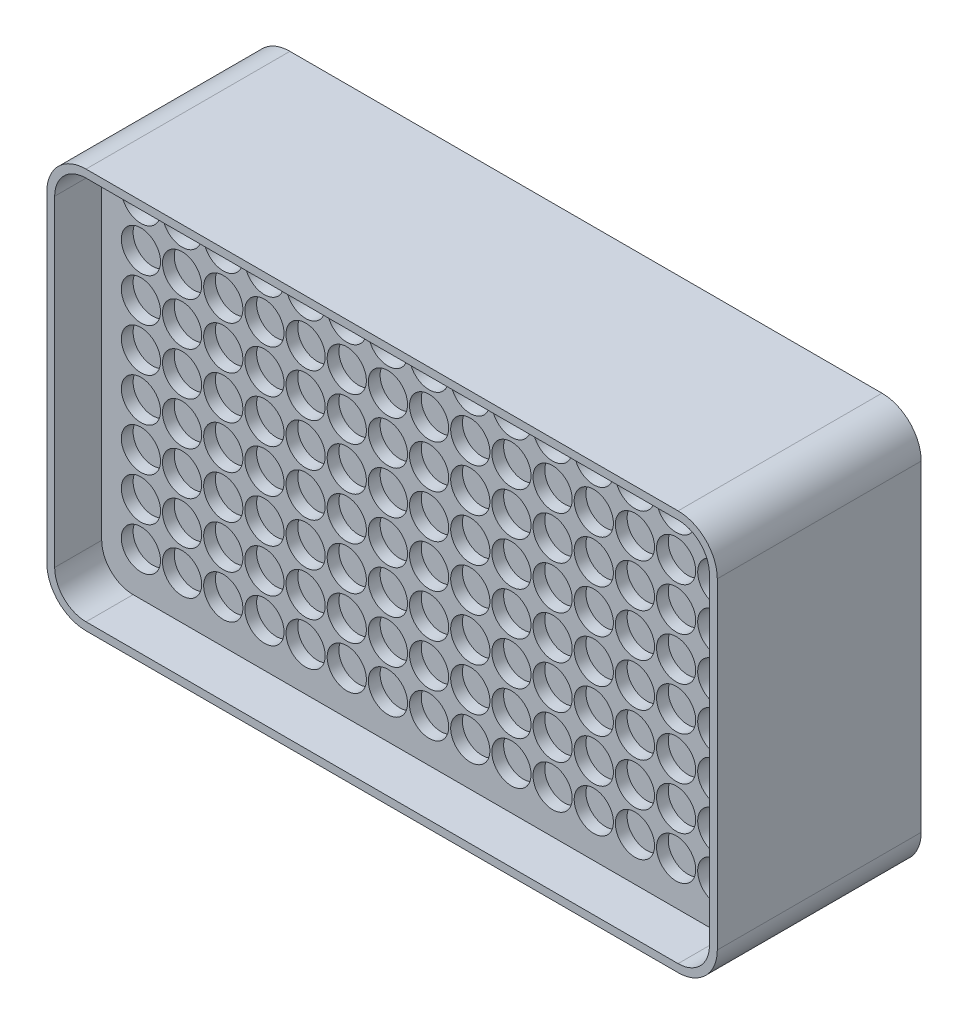
SolidWorks part; units mm, degrees
ref_plane "Front Plane" through (0, 0, 0) normal (0, 0, 1) x (1, 0, 0)
ref_plane "Top Plane" through (0, 0, 0) normal (0, 1, 0) x (1, 0, 0)
ref_plane "Right Plane" through (0, 0, 0) normal (1, 0, 0) x (0, 0, -1)
sketch "Sketch1" plane through (0, 0, 0) normal (0, 0, 1) x (1, 0, 0)
  line L1 (85.5, 51) -> (-85.5, 51)
  line L2 (85.5, 51) -> (85.5, -51)
  line L3 (85.5, -51) -> (-85.5, -51)
  line L4 (-85.5, 51) -> (-85.5, -51)
  line L5 (85.5, 51) -> (-85.5, -51) construction
  line L6 (85.5, -51) -> (-85.5, 51) construction
  point P0 (0, 0)
  dimension "D1" = 171
  dimension "D2" = 102
extrude "Boss-Extrude1" add sketch "Sketch1" along normal blind 40
fillet "Fillet1" radius 10 4 edges at (85.5, -51, 20) (85.5, 51, 20) (-85.5, -51, 20) (-85.5, 51, 20)
sketch "Sketch3" plane through (0, 0, 40) normal (0, 0, 1) x (1, 0, 0)
  line L0 (75.5, 51) -> (-75.5, 51) construction
  line L1 (-85.5, 41) -> (-85.5, -41) construction
  line L2 (-73.5, 39) -> (-63, 39) construction
  circle A0 centre (-73.5, 39) radius 5
  circle A1 centre (-63, 39) radius 5
  circle A2 centre (-52.5, 39) radius 5
  circle A3 centre (-42, 39) radius 5
  circle A4 centre (-31.5, 39) radius 5
  circle A5 centre (-21, 39) radius 5
  circle A6 centre (-10.5, 39) radius 5
  circle A7 centre (0, 39) radius 5
  circle A8 centre (10.5, 39) radius 5
  circle A9 centre (21, 39) radius 5
  circle A10 centre (31.5, 39) radius 5
  circle A11 centre (42, 39) radius 5
  circle A12 centre (52.5, 39) radius 5
  circle A13 centre (63, 39) radius 5
  circle A14 centre (73.5, 39) radius 5
  circle A15 centre (-63, 28) radius 5
  circle A16 centre (-52.5, 28) radius 5
  circle A17 centre (-42, 28) radius 5
  circle A18 centre (-31.5, 28) radius 5
  circle A19 centre (-21, 28) radius 5
  circle A20 centre (-10.5, 28) radius 5
  circle A21 centre (0, 28) radius 5
  circle A22 centre (10.5, 28) radius 5
  circle A23 centre (21, 28) radius 5
  circle A24 centre (31.5, 28) radius 5
  circle A25 centre (42, 28) radius 5
  circle A26 centre (52.5, 28) radius 5
  circle A27 centre (63, 28) radius 5
  circle A28 centre (73.5, 28) radius 5
  circle A29 centre (-63, 17) radius 5
  circle A30 centre (-52.5, 17) radius 5
  circle A31 centre (-42, 17) radius 5
  circle A32 centre (-31.5, 17) radius 5
  circle A33 centre (-21, 17) radius 5
  circle A34 centre (-10.5, 17) radius 5
  circle A35 centre (0, 17) radius 5
  circle A36 centre (10.5, 17) radius 5
  circle A37 centre (21, 17) radius 5
  circle A38 centre (31.5, 17) radius 5
  circle A39 centre (42, 17) radius 5
  circle A40 centre (52.5, 17) radius 5
  circle A41 centre (63, 17) radius 5
  circle A42 centre (73.5, 17) radius 5
  circle A43 centre (-63, 6) radius 5
  circle A44 centre (-52.5, 6) radius 5
  circle A45 centre (-42, 6) radius 5
  circle A46 centre (-31.5, 6) radius 5
  circle A47 centre (-21, 6) radius 5
  circle A48 centre (-10.5, 6) radius 5
  circle A49 centre (0, 6) radius 5
  circle A50 centre (10.5, 6) radius 5
  circle A51 centre (21, 6) radius 5
  circle A52 centre (31.5, 6) radius 5
  circle A53 centre (42, 6) radius 5
  circle A54 centre (52.5, 6) radius 5
  circle A55 centre (63, 6) radius 5
  circle A56 centre (73.5, 6) radius 5
  circle A57 centre (-63, -5) radius 5
  circle A58 centre (-52.5, -5) radius 5
  circle A59 centre (-42, -5) radius 5
  circle A60 centre (-31.5, -5) radius 5
  circle A61 centre (-21, -5) radius 5
  circle A62 centre (-10.5, -5) radius 5
  circle A63 centre (0, -5) radius 5
  circle A64 centre (10.5, -5) radius 5
  circle A65 centre (21, -5) radius 5
  circle A66 centre (31.5, -5) radius 5
  circle A67 centre (42, -5) radius 5
  circle A68 centre (52.5, -5) radius 5
  circle A69 centre (63, -5) radius 5
  circle A70 centre (73.5, -5) radius 5
  circle A71 centre (-63, -16) radius 5
  circle A72 centre (-52.5, -16) radius 5
  circle A73 centre (-42, -16) radius 5
  circle A74 centre (-31.5, -16) radius 5
  circle A75 centre (-21, -16) radius 5
  circle A76 centre (-10.5, -16) radius 5
  circle A77 centre (0, -16) radius 5
  circle A78 centre (10.5, -16) radius 5
  circle A79 centre (21, -16) radius 5
  circle A80 centre (31.5, -16) radius 5
  circle A81 centre (42, -16) radius 5
  circle A82 centre (52.5, -16) radius 5
  circle A83 centre (63, -16) radius 5
  circle A84 centre (73.5, -16) radius 5
  circle A85 centre (-63, -27) radius 5
  circle A86 centre (-52.5, -27) radius 5
  circle A87 centre (-42, -27) radius 5
  circle A88 centre (-31.5, -27) radius 5
  circle A89 centre (-21, -27) radius 5
  circle A90 centre (-10.5, -27) radius 5
  circle A91 centre (0, -27) radius 5
  circle A92 centre (10.5, -27) radius 5
  circle A93 centre (21, -27) radius 5
  circle A94 centre (31.5, -27) radius 5
  circle A95 centre (42, -27) radius 5
  circle A96 centre (52.5, -27) radius 5
  circle A97 centre (63, -27) radius 5
  circle A98 centre (73.5, -27) radius 5
  circle A99 centre (-63, -38) radius 5
  circle A100 centre (-52.5, -38) radius 5
  circle A101 centre (-42, -38) radius 5
  circle A102 centre (-31.5, -38) radius 5
  circle A103 centre (-21, -38) radius 5
  circle A104 centre (-10.5, -38) radius 5
  circle A105 centre (0, -38) radius 5
  circle A106 centre (10.5, -38) radius 5
  circle A107 centre (21, -38) radius 5
  circle A108 centre (31.5, -38) radius 5
  circle A109 centre (42, -38) radius 5
  circle A110 centre (52.5, -38) radius 5
  circle A111 centre (63, -38) radius 5
  circle A112 centre (73.5, -38) radius 5
  circle A113 centre (-73.5, 28) radius 5
  circle A114 centre (-73.5, 17) radius 5
  circle A115 centre (-73.5, 6) radius 5
  circle A116 centre (-73.5, -5) radius 5
  circle A117 centre (-73.5, -16) radius 5
  circle A118 centre (-73.5, -27) radius 5
  circle A119 centre (-73.5, -38) radius 5
  dimension "D1" = 10
  dimension "D2" = 12
  dimension "D3" = 12
  dimension "D6" = 10.5
  dimension "D4" = 15
  dimension "D5" = 8
extrude "Cut-Extrude1" cut sketch "Sketch3" against normal blind 3
sketch "Sketch5" plane through (0, 0, 40) normal (0, 0, 1) x (1, 0, 0)
  line L0 (-75.5, 49) -> (75.5, 49)
  line L1 (-75.5, 51) -> (75.5, 51)
  line L2 (-85.5, 41) -> (-85.5, -41)
  line L3 (-75.5, -51) -> (75.5, -51)
  line L4 (85.5, 41) -> (85.5, -41)
  line L5 (-85.5, 51) -> (85.5, -51) construction
  line L6 (-85.5, -51) -> (85.5, 51) construction
  line L7 (83.5, 41) -> (83.5, -41)
  line L8 (-75.5, -49) -> (75.5, -49)
  line L9 (-83.5, 41) -> (-83.5, -41)
  arc A0 (75.5, -51) -> (85.5, -41) centre (75.5, -41) ccw
  arc A1 (-85.5, -41) -> (-75.5, -51) centre (-75.5, -41) ccw
  arc A2 (-75.5, 51) -> (-85.5, 41) centre (-75.5, 41) ccw
  arc A3 (75.5, 51) -> (85.5, 41) centre (75.5, 41) cw
  arc A4 (75.5, 49) -> (83.5, 41) centre (75.5, 41) cw
  arc A5 (75.5, -49) -> (83.5, -41) centre (75.5, -41) ccw
  arc A6 (-83.5, -41) -> (-75.5, -49) centre (-75.5, -41) ccw
  arc A7 (-75.5, 49) -> (-83.5, 41) centre (-75.5, 41) ccw
  point P0 (0, 0)
  dimension "D3" = 10
  dimension "D1" = 171
  dimension "D2" = 102
  dimension "D4" = 2
extrude "Boss-Extrude4" add sketch "Sketch5" along normal blind 12
